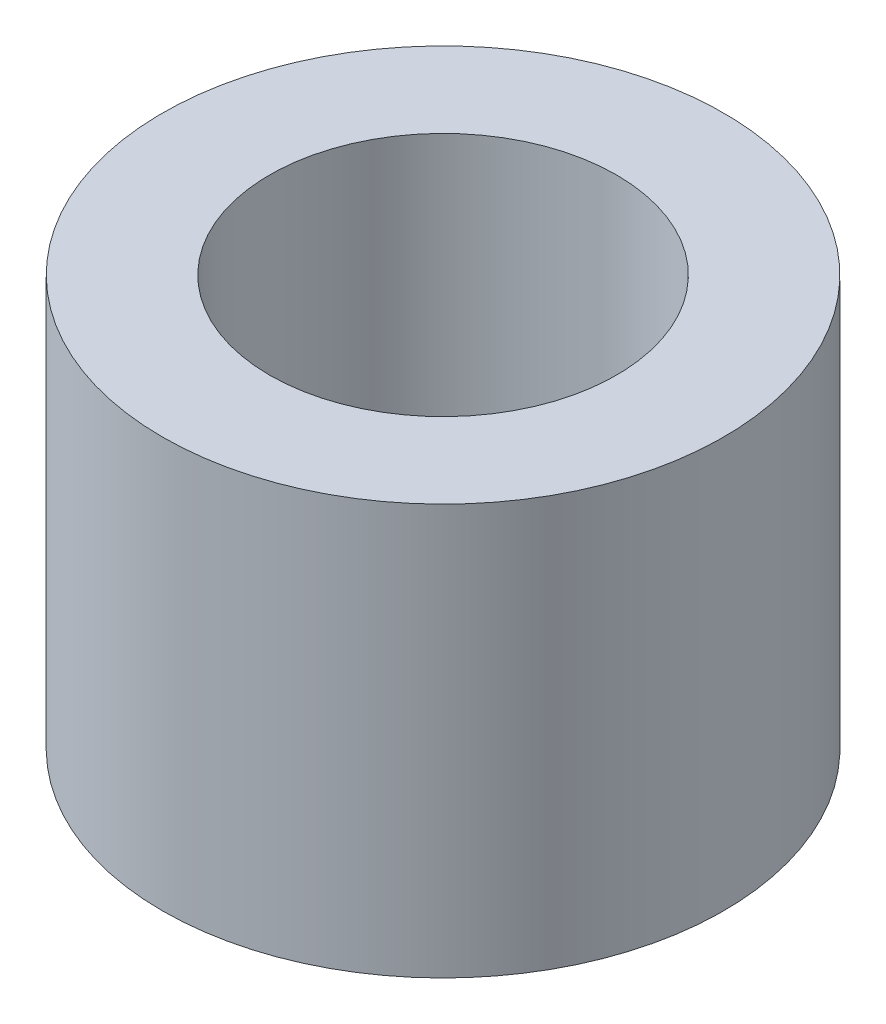
SolidWorks part; units mm, degrees
ref_plane "Front Plane" through (0, 0, 0) normal (0, 0, 1) x (1, 0, 0)
ref_plane "Top Plane" through (0, 0, 0) normal (0, 1, 0) x (1, 0, 0)
ref_plane "Right Plane" through (0, 0, 0) normal (1, 0, 0) x (0, 0, -1)
sketch "Sketch1" plane through (0, 0, 0) normal (0, 1, 0) x (1, 0, 0)
  circle A0 centre (0, 0) radius 3.2375
  circle A1 centre (0, 0) radius 5.2375
  dimension "D1" = 6.475
  dimension "D2" = 2
extrude "Boss-Extrude1" add sketch "Sketch1" along normal blind 7.6596 contours A1 | A0
